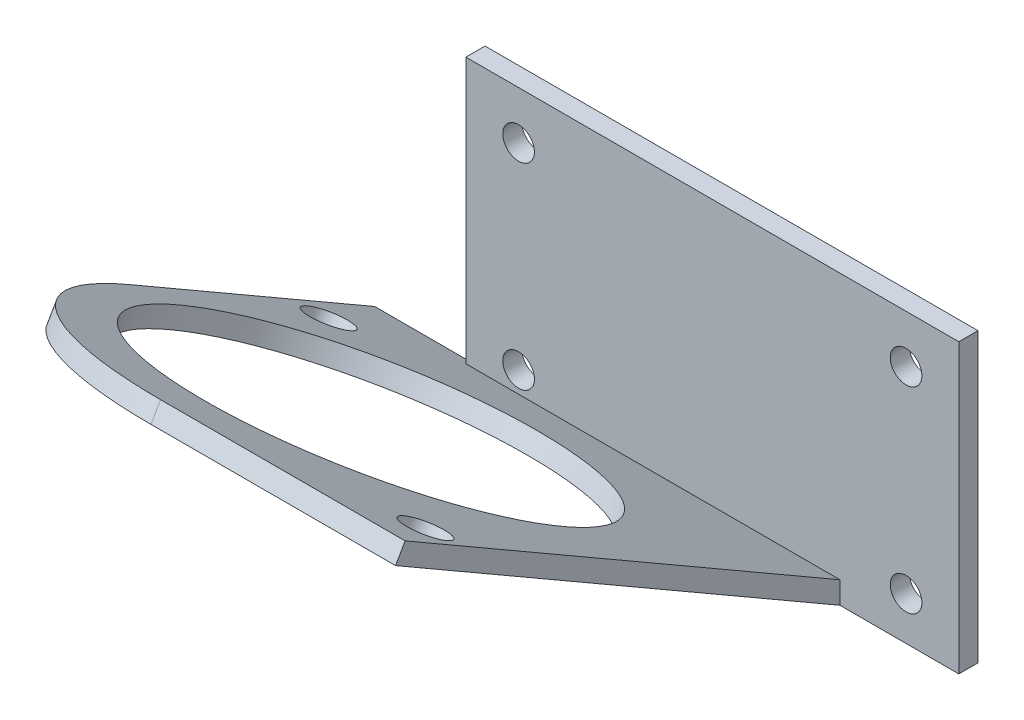
SolidWorks part; units mm, degrees
material "PTFE (general)"
ref_plane "Front Plane" through (0, 0, 0) normal (0, 0, 1) x (1, 0, 0)
ref_plane "Top Plane" through (0, 0, 0) normal (0, 1, 0) x (1, 0, 0)
ref_plane "Right Plane" through (0, 0, 0) normal (1, 0, 0) x (0, 0, -1)
sketch "Sketch1" plane through (0, 0, 0) normal (0, 0, 1) x (1, 0, 0)
  line L1 (0, 0) -> (51.4, 0)
  line L2 (0, 0) -> (0, 30)
  line L3 (0, 30) -> (51.4, 30)
  line L4 (51.4, 0) -> (51.4, 30)
  line L5 (0, 0) -> (51.4, 30) construction
  line L6 (0, 30) -> (51.4, 0) construction
  point P4 (25.7, 15)
  dimension "D1" = 51.4
  dimension "D2" = 30
extrude "Boss-Extrude1" add sketch "Sketch1" along normal blind 2
sketch "Sketch2" plane through (0, 0, 0) normal (0, 0, -1) x (-1, 0, 0)
  circle A0 centre (-45.9, 25) radius 1.65
  circle A1 centre (-5.5, 25) radius 1.65
  circle A2 centre (-5.5, 4.5) radius 1.65
  circle A3 centre (-45.9, 4.5) radius 1.65
  dimension "D1" = 3.3
extrude "Cut-Extrude1" cut sketch "Sketch2" against normal blind 10
ref_plane "Plane1" through (0, -0.866, 0.5) normal (0, -0.866, 0.5) x (1, 0, 0)
sketch "Sketch3" plane through (0, -0.866, 0.5) normal (0, -0.866, 0.5) x (1, 0, 0)
  line L0 (0, 16.7321) -> (0, 1.7321) construction
  line L1 (39, 1.7321) -> (-10.5, 1.7321)
  line L2 (39, 1.7321) -> (39, 55.2321)
  line L3 (39, 55.2321) -> (-10.5, 55.2321)
  line L4 (-10.5, 1.7321) -> (-10.5, 55.2321)
  line L5 (39, 1.7321) -> (-10.5, 55.2321) construction
  line L6 (39, 55.2321) -> (-10.5, 1.7321) construction
  line L9 (0, 1.7321) -> (51.4, 1.7321) construction
  point P4 (14.25, 28.4821)
  dimension "D1" = 49.5
  dimension "D2" = 53.5
  dimension "D3" = 10.5
extrude "Boss-Extrude2" add sketch "Sketch3" against normal blind 2
fillet "Fillet1" radius 24 1 edges at (-10.5, 27.616, 47.8324)
sketch "Sketch5" plane through (0, -0.866, 0.5) normal (0, -0.866, 0.5) x (1, 0, 0)
  circle A0 centre (35.9, 49.2108) radius 2.25
  circle A1 centre (-7.1, 11.2108) radius 2.25
extrude "Cut-Extrude2" cut sketch "Sketch5" against normal blind 2
sketch "Sketch6" plane through (0, -0.866, 0.5) normal (0, -0.866, 0.5) x (1, 0, 0)
  circle A0 centre (12.9, 29.2108) radius 20
  dimension "D1" = 40
extrude "Cut-Extrude3" cut sketch "Sketch6" against normal blind 2
